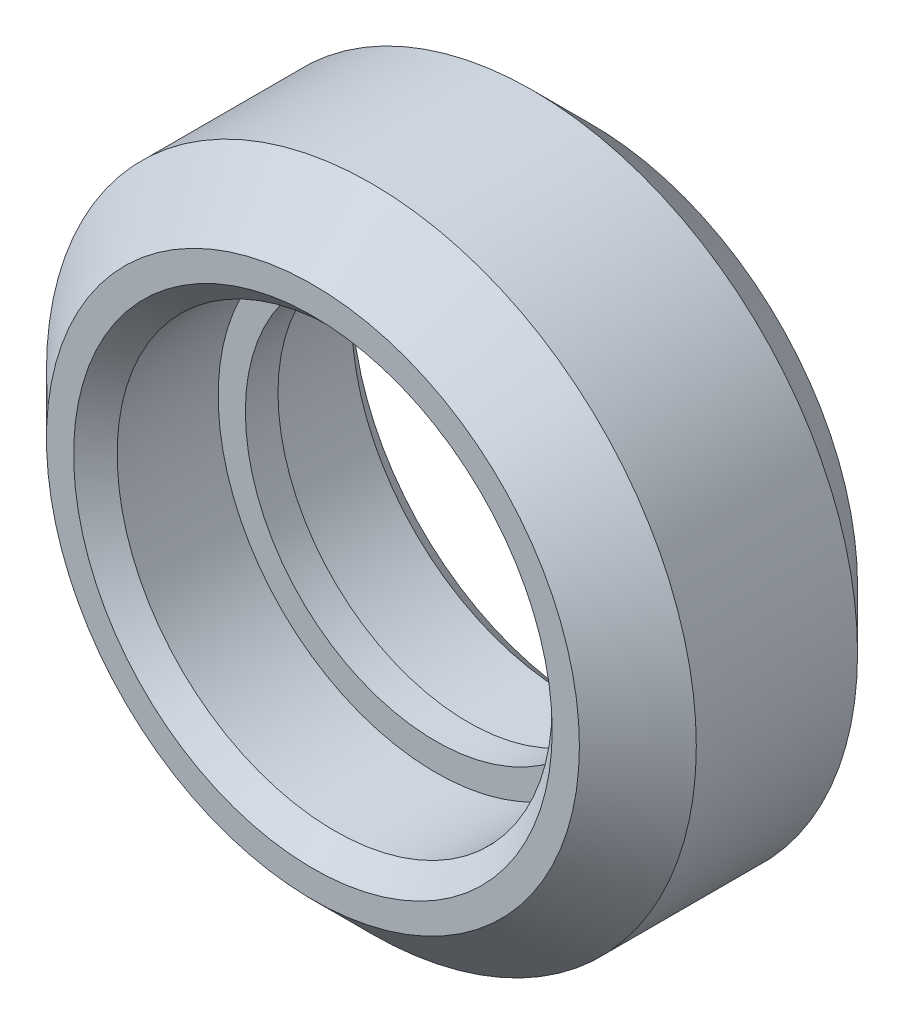
SolidWorks part; units mm, degrees
material "PA Type 6"
ref_plane "Спереди" through (0, 0, 0) normal (0, 0, 1) x (1, 0, 0)
ref_plane "Сверху" through (0, 0, 0) normal (0, 1, 0) x (1, 0, 0)
ref_plane "Справа" through (0, 0, 0) normal (1, 0, 0) x (0, 0, -1)
sketch "Эскиз1" plane through (0, 0, 0) normal (0, 0, 1) x (1, 0, 0)
  circle A0 centre (0, 0) radius 11.95
  dimension "D1" = 23.9
extrude "Бобышка-Вытянуть1" add sketch "Эскиз1" along normal blind 10.23
sketch "Эскиз2" plane through (0, 0, 10.23) normal (0, 0, 1) x (1, 0, 0)
  circle A0 centre (0, 0) radius 7
  dimension "D1" = 14
extrude "Вырез-Вытянуть1" cut sketch "Эскиз2" against normal through all
chamfer "Фаска1" distance 2.15 angle 45 2 edges at (11.95, 0, 0) (11.95, 0, 10.23)
ref_plane "Плоскость1" through (0, 0, 5.115) normal (0, 0, -1) x (-1, 0, 0)
sketch "Эскиз3" plane through (0, 0, 10.23) normal (0, 0, 1) x (1, 0, 0)
  circle A0 centre (0, 0) radius 8
  dimension "D1" = 16
extrude "Вырез-Вытянуть2" cut sketch "Эскиз3" against normal blind 4.515
mirror "Зеркальное отражение1" about plane through (0, 0, 5.115) normal (0, 0, -1) of "Вырез-Вытянуть2"
chamfer "Фаска2" distance 0.8 angle 45 2 edges at (8, 0, 0) (8, 0, 10.23)
